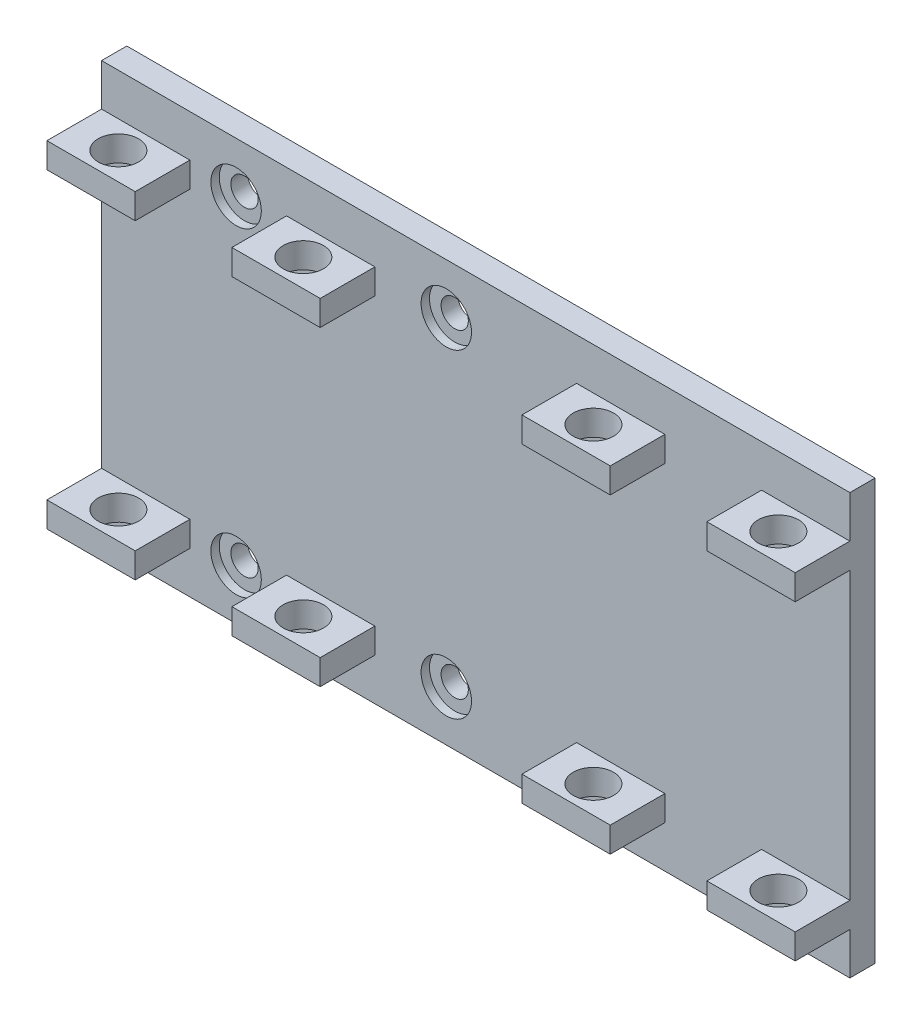
SolidWorks part; units mm, degrees
ref_plane "前视基准面" through (0, 0, 0) normal (0, 0, 1) x (1, 0, 0)
ref_plane "上视基准面" through (0, 0, 0) normal (0, 1, 0) x (1, 0, 0)
ref_plane "右视基准面" through (0, 0, 0) normal (1, 0, 0) x (0, 0, -1)
sketch "草图1" plane through (0, 0, 0) normal (0, 0, 1) x (1, 0, 0)
  line L1 (-117.1466, 42.22) -> (-28.1466, 42.22)
  line L2 (-117.1466, 42.22) -> (-117.1466, 2.22)
  line L3 (-117.1466, 2.22) -> (-28.1466, 2.22)
  line L4 (-28.1466, 42.22) -> (-28.1466, 2.22)
  dimension "D1" = 89
  dimension "D2" = 40
extrude "凸台-拉伸1" add sketch "草图1" along normal blind 3
sketch "草图2" plane through (0, 0, 3) normal (0, 0, 1) x (1, 0, 0)
  line L1 (-117.1466, 42.22) -> (-84.6466, 42.22)
  line L2 (-117.1466, 42.22) -> (-117.1466, 39.22)
  line L3 (-117.1466, 39.22) -> (-84.6466, 39.22)
  line L4 (-84.6466, 42.22) -> (-84.6466, 39.22)
  line L5 (-117.1466, 2.22) -> (-84.6466, 2.22)
  line L6 (-117.1466, 2.22) -> (-117.1466, 5.22)
  line L7 (-117.1466, 5.22) -> (-84.6466, 5.22)
  line L8 (-84.6466, 2.22) -> (-84.6466, 5.22)
  line L9 (-28.1466, 42.22) -> (-60.6466, 42.22)
  line L10 (-28.1466, 42.22) -> (-28.1466, 39.22)
  line L11 (-28.1466, 39.22) -> (-60.6466, 39.22)
  line L12 (-60.6466, 42.22) -> (-60.6466, 39.22)
  line L13 (-28.1466, 2.22) -> (-60.6466, 2.22)
  line L14 (-28.1466, 2.22) -> (-28.1466, 5.22)
  line L15 (-28.1466, 5.22) -> (-60.6466, 5.22)
  line L16 (-60.6466, 2.22) -> (-60.6466, 5.22)
  dimension "D1" = 3
  dimension "D2" = 32.5
  dimension "D3" = 3
  dimension "D4" = 32.5
  dimension "D5" = 3
  dimension "D6" = 32.5
  dimension "D7" = 3
  dimension "D8" = 32.5
extrude "凸台-拉伸2" add sketch "草图2" along normal blind 6.5
sketch "草图3" plane through (0, 2.22, 0) normal (0, -1, 0) x (-1, 0, 0)
  line L0 (117.1466, -9.5) -> (84.6466, -9.5) construction
  line L2 (117.1466, -9.5) -> (117.1466, 0) construction
  line L3 (84.6466, -9.5) -> (84.6466, -3) construction
  line L4 (60.6466, -9.5) -> (60.6466, -3) construction
  line L5 (28.1466, -9.5) -> (28.1466, 0) construction
  circle A0 centre (111.8966, -6.25) radius 2.4
  circle A1 centre (89.8966, -6.25) radius 2.4
  circle A2 centre (55.3966, -6.25) radius 2.4
  circle A3 centre (33.3966, -6.25) radius 2.4
  dimension "D1" = 3.25
  dimension "D2" = 5.25
  dimension "D3" = 5.25
  dimension "D4" = 5.25
  dimension "D5" = 5.25
extrude "切除-拉伸1" cut sketch "草图3" against normal blind 100
sketch "草图5" plane through (-117.1466, 0, 0) normal (-1, 0, 0) x (0, 0, 1)
  line L1 (0, 42.22) -> (3, 42.22)
  line L2 (0, 42.22) -> (0, 47.22)
  line L3 (0, 47.22) -> (3, 47.22)
  line L4 (3, 42.22) -> (3, 47.22)
  line L5 (0, 2.22) -> (3, 2.22)
  line L6 (0, 2.22) -> (0, -2.78)
  line L7 (0, -2.78) -> (3, -2.78)
  line L8 (3, 2.22) -> (3, -2.78)
  dimension "D1" = 5
  dimension "D2" = 5
extrude "凸台-拉伸3" add sketch "草图5" against normal up to surface (89 mm away) up to face at (-28.1466, 22.22, 5.5)
sketch "草图7" plane through (0, 0, 9.5) normal (0, 0, 1) x (1, 0, 0)
  line L0 (-28.1466, 47.22) -> (-117.1466, 47.22) construction
  line L1 (-106.6466, 47.22) -> (-95.1466, 47.22)
  line L2 (-106.6466, 47.22) -> (-106.6466, -2.78)
  line L3 (-106.6466, -2.78) -> (-95.1466, -2.78)
  line L4 (-95.1466, 47.22) -> (-95.1466, -2.78)
  line L5 (-28.1466, -2.78) -> (-117.1466, -2.78) construction
  line L6 (-117.1466, 39.22) -> (-117.1466, 5.22) construction
  line L7 (-84.6466, 2.22) -> (-84.6466, 5.22) construction
  line L8 (-60.6466, 5.22) -> (-60.6466, 2.22) construction
  line L9 (-50.1466, 47.22) -> (-38.6466, 47.22)
  line L10 (-50.1466, 47.22) -> (-50.1466, -2.78)
  line L11 (-50.1466, -2.78) -> (-38.6466, -2.78)
  line L12 (-38.6466, 47.22) -> (-38.6466, -2.78)
  line L13 (-28.1466, 5.22) -> (-28.1466, 39.22) construction
  dimension "D1" = 10.5
  dimension "D2" = 10.5
  dimension "D3" = 10.5
  dimension "D4" = 10.5
extrude "切除-拉伸2" cut sketch "草图7" against normal up to surface (6.5 mm away) up to face at (-72.6466, 22.22, 3)
sketch "草图8" plane through (0, 0, 0) normal (0, 0, -1) x (-1, 0, 0)
  line L0 (28.1466, 47.22) -> (117.1466, 47.22) construction
  line L2 (117.1466, 47.22) -> (117.1466, -2.78) construction
  line L3 (28.1466, -2.78) -> (117.1466, -2.78) construction
  circle A0 centre (101.1466, 41.22) radius 1.62
  circle A1 centre (101.1466, 3.22) radius 1.62
  circle A2 centre (76.1466, 41.22) radius 1.62
  circle A3 centre (76.1466, 3.22) radius 1.62
  dimension "D1" = 3.24
  dimension "D2" = 6
  dimension "D3" = 16
  dimension "D4" = 3.24
  dimension "D5" = 6
  dimension "D6" = 16
  dimension "D7" = 3.24
  dimension "D8" = 25
  dimension "D9" = 3.24
  dimension "D10" = 6
  dimension "D11" = 6
  dimension "D12" = 25
extrude "切除-拉伸3" cut sketch "草图8" against normal through all
sketch "草图9" plane through (0, 0, 3) normal (0, 0, 1) x (1, 0, 0)
  circle A0 centre (-76.1466, 41.22) radius 3
  circle A1 centre (-101.1466, 41.22) radius 3
  circle A2 centre (-101.1466, 3.22) radius 3
  circle A3 centre (-76.1466, 3.22) radius 3
extrude "切除-拉伸4" cut sketch "草图9" against normal blind 1
